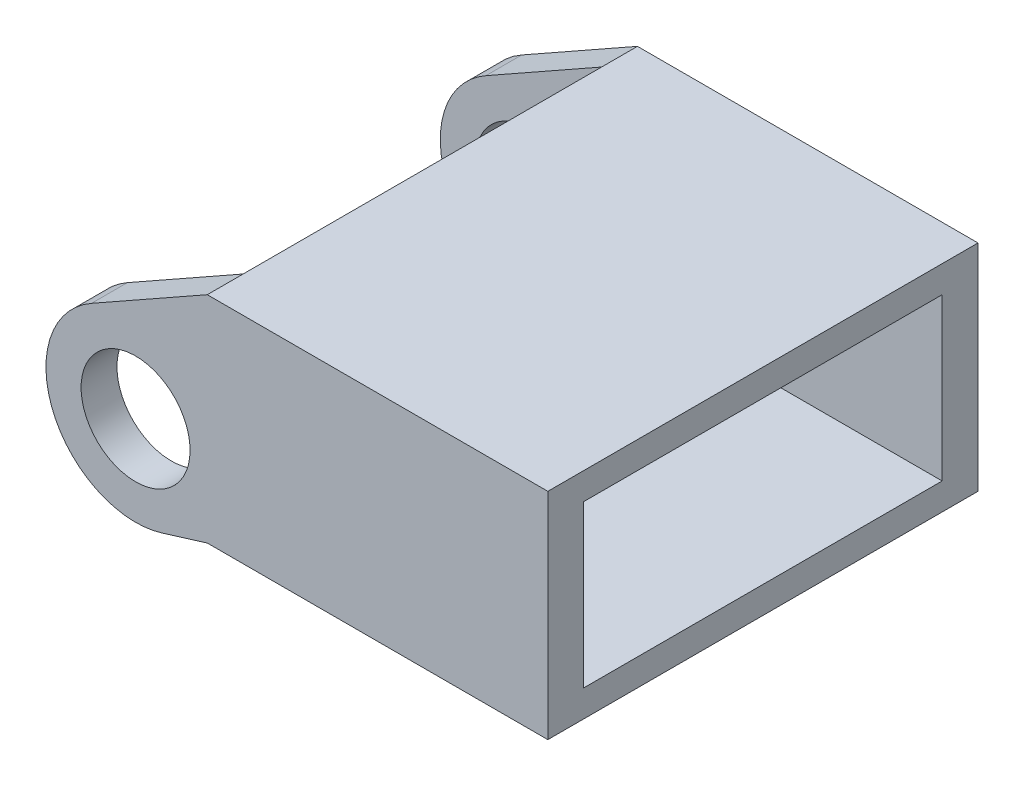
SolidWorks part; units mm, degrees
ref_plane "Front Plane" through (0, 0, 0) normal (0, 0, 1) x (1, 0, 0)
ref_plane "Top Plane" through (0, 0, 0) normal (0, 1, 0) x (1, 0, 0)
ref_plane "Right Plane" through (0, 0, 0) normal (1, 0, 0) x (0, 0, -1)
sketch "Sketch2" plane through (0, 0, 0) normal (0, 0, 1) x (1, 0, 0)
  line L0 (0, 12.7) -> (-12.7, 12.7) construction
  line L1 (0, 0) -> (60.325, 0)
  line L2 (0, 0) -> (0, 38.1) construction
  line L3 (0, 38.1) -> (60.325, 38.1)
  line L4 (60.325, 0) -> (60.325, 38.1)
  line L5 (-20.5045, 26.5241) -> (0, 38.1)
  line L6 (-8.0283, -2.472) -> (0, 0)
  arc A0 (-20.5045, 26.5241) -> (-8.0283, -2.472) centre (-12.7, 12.7) ccw
  point P9 (0, 19.05)
  dimension "D4" = 15.875
  dimension "D1" = 60.325
  dimension "D2" = 38.1
  dimension "D3" = 12.7
  dimension "D5" = 6.35
extrude "Mass" add sketch "Sketch2" along normal blind 76.2
sketch "Sketch17" plane through (60.325, 0, 0) normal (1, 0, 0) x (0, 0, -1)
  line L0 (-76.2, 0) -> (-76.2, 38.1) construction
  line L1 (-6.35, 33.3375) -> (-69.85, 33.3375)
  line L2 (-6.35, 33.3375) -> (-6.35, 4.7625)
  line L3 (-6.35, 4.7625) -> (-69.85, 4.7625)
  line L4 (-69.85, 33.3375) -> (-69.85, 4.7625)
  line L5 (0, 0) -> (0, 38.1) construction
  line L6 (-76.2, 0) -> (0, 0) construction
  line L7 (-76.2, 38.1) -> (0, 38.1) construction
  dimension "D1" = 6.35
  dimension "D2" = 6.35
  dimension "D3" = 4.7625
  dimension "D4" = 4.7625
extrude "Hollow1" cut sketch "Sketch17" against normal through all
sketch "Sketch19" plane through (0, 38.1, 0) normal (0, 1, 0) x (1, 0, 0)
  line L0 (0, -76.2) -> (0, 0) construction
  line L1 (0, -6.35) -> (-50.8, -6.35)
  line L2 (0, -6.35) -> (0, -69.85)
  line L3 (0, -69.85) -> (-50.8, -69.85)
  line L4 (-50.8, -6.35) -> (-50.8, -69.85)
  line L5 (-8.4359, -69.85) -> (-20.5045, -69.85) construction
  line L6 (-20.5045, -6.35) -> (-8.4359, -6.35) construction
  dimension "D1" = 50.8
extrude "Hollow2" cut sketch "Sketch19" against normal through all
sketch "Sketch20" plane through (0, 0, 76.2) normal (0, 0, 1) x (1, 0, 0)
  circle A0 centre (-12.7, 12.7) radius 9.652
  arc A1 (-20.5045, 26.5241) -> (-8.0283, -2.472) centre (-12.7, 12.7) ccw construction
  dimension "D1" = 19.304
extrude "Horiz. Bearing Mount" cut sketch "Sketch20" against normal through all
